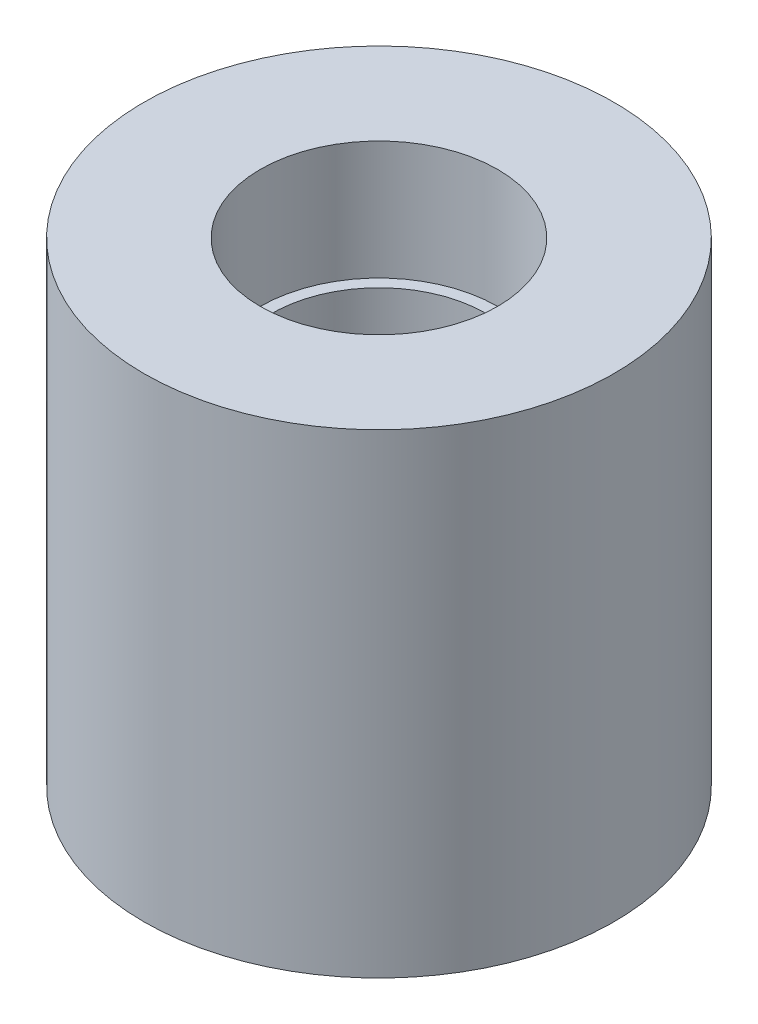
SolidWorks part; units mm, degrees
material "ABS PC"
ref_plane "Front Plane" through (0, 0, 0) normal (0, 0, 1) x (1, 0, 0)
ref_plane "Top Plane" through (0, 0, 0) normal (0, 1, 0) x (1, 0, 0)
ref_plane "Right Plane" through (0, 0, 0) normal (1, 0, 0) x (0, 0, -1)
sketch "Sketch1" plane through (0, 0, 0) normal (0, 1, 0) x (1, 0, 0)
  circle A0 centre (0, 0) radius 12.573
  circle A1 centre (0, 0) radius 5.715
  dimension "D1" = 11.43
  dimension "D2" = 25.146
extrude "Boss-Extrude1" add sketch "Sketch1" along normal blind 25.4
sketch "Sketch3" plane through (0, 25.4, 0) normal (0, 1, 0) x (1, 0, 0)
  circle A0 centre (0, 0) radius 5.715
  circle A1 centre (0, 0) radius 6.35
extrude "Cut-Extrude2" cut sketch "Sketch3" against normal blind 6.35
sketch "Sketch4" plane through (0, 0, 0) normal (0, -1, 0) x (1, 0, 0)
  circle A0 centre (0, 0) radius 5.715
  circle A1 centre (0, 0) radius 6.35
extrude "Cut-Extrude3" cut sketch "Sketch4" against normal blind 6.35
